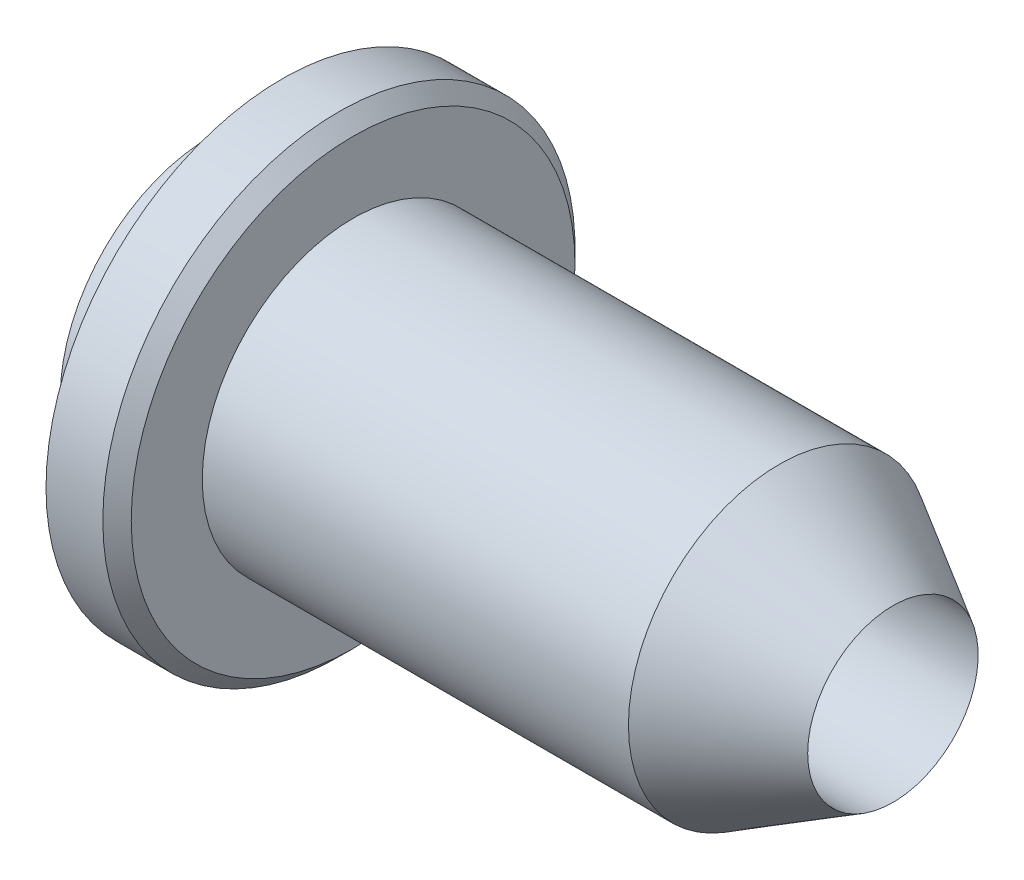
SolidWorks part; units mm, degrees
material "AISI 316 Stainless Steel Sheet (SS)"
ref_plane "Front Plane" through (0, 0, 0) normal (0, 0, 1) x (1, 0, 0)
ref_plane "Top Plane" through (0, 0, 0) normal (0, 1, 0) x (1, 0, 0)
ref_plane "Right Plane" through (0, 0, 0) normal (1, 0, 0) x (0, 0, -1)
sketch "Sketch1" plane through (0, 0, 0) normal (0, 0, 1) x (1, 0, 0)
  line L0 (0, 0) -> (48, 0) construction
  line L1 (48, 6) -> (48, -6)
  line L2 (48, -6) -> (40, -10.6188)
  line L3 (48, 6) -> (40, 10.6188)
  line L4 (48, -5) -> (1, -5)
  line L5 (48, 5) -> (1, 5)
  line L6 (40, -10.6188) -> (10, -10.6188)
  line L7 (40, 10.6188) -> (10, 10.6188)
  line L9 (48, -6) -> (10, -6) construction
  line L10 (0, 10.6188) -> (0, 6)
  line L11 (48, -6) -> (0, -6)
  line L12 (48, 6) -> (0, 6)
  line L13 (0, -6) -> (0, -10.6188)
  line L14 (0, 6) -> (1, 5)
  line L15 (1, -5) -> (0, -6)
  line L16 (48, 6) -> (10, 6) construction
  line L17 (10, -6) -> (10, -10.6188) construction
  line L18 (10, 6) -> (10, 10.6188) construction
  line L19 (5, -10.6188) -> (0, -10.6188)
  line L21 (10, -10.6188) -> (10, -15.6188)
  line L22 (9, -16.6188) -> (5, -16.6188)
  line L23 (5, -10.6188) -> (5, -16.6188)
  line L25 (10, 10.6188) -> (10, 15.6188)
  line L26 (9, 16.6188) -> (5, 16.6188)
  line L27 (5, 10.6188) -> (5, 16.6188)
  line L28 (5, 10.6188) -> (0, 10.6188)
  line L29 (10, -15.6188) -> (9, -16.6188)
  line L30 (10, 15.6188) -> (9, 16.6188)
  point P17 (0, 5)
  point P20 (0, -5)
  point P24 (10, -16.6188)
  point P27 (10, 16.6188)
  dimension "D1" = 48
  dimension "D2" = 12
  dimension "D3" = 8
  dimension "D4" = 120
  dimension "D5" = 120
  dimension "D6" = 8
  dimension "D7" = 5
  dimension "D8" = 5
  dimension "D9" = 38
  dimension "D10" = 40
  dimension "D11" = 1
  dimension "D12" = 45
  dimension "D13" = 1
  dimension "D14" = 45
  dimension "D15" = 38
  dimension "D16" = 6
  dimension "D17" = 5
  dimension "D18" = 6
  dimension "D19" = 5
  dimension "D20" = 1
  dimension "D21" = 45
  dimension "D22" = 1
  dimension "D23" = 45
revolve "Revolve1" add sketch "Sketch1" angle 360 about L0
